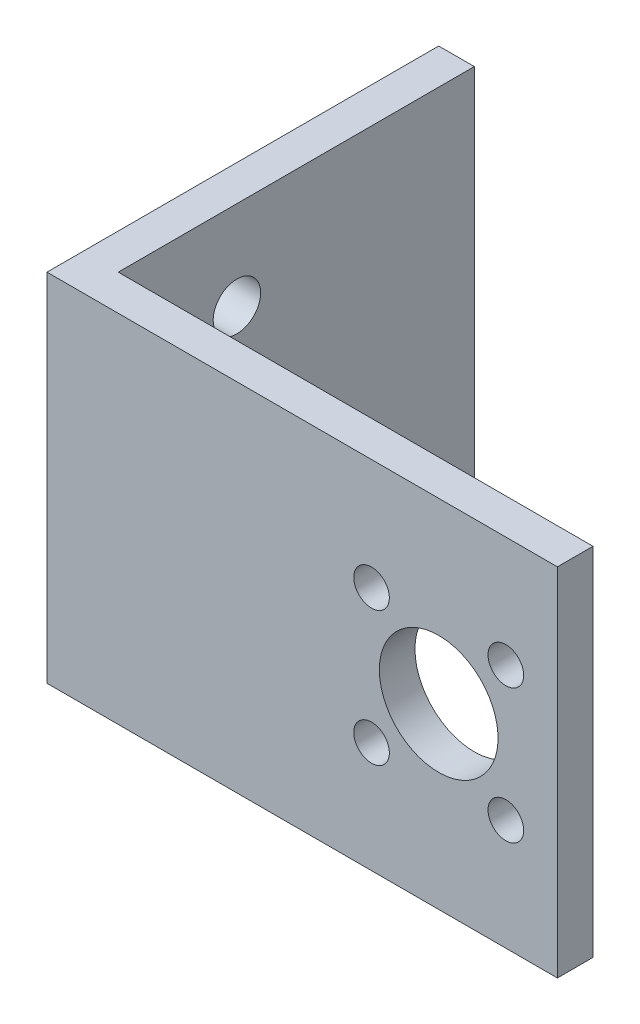
SolidWorks part; units mm, degrees
ref_plane "前视基准面" through (0, 0, 0) normal (0, 0, 1) x (1, 0, 0)
ref_plane "上视基准面" through (0, 0, 0) normal (0, 1, 0) x (1, 0, 0)
ref_plane "右视基准面" through (0, 0, 0) normal (1, 0, 0) x (0, 0, -1)
sketch "草图2" plane through (0, 0, 0) normal (0, 1, 0) x (1, 0, 0)
  line L0 (0, 0) -> (43, 0)
  line L1 (43, 0) -> (43, 3)
  line L2 (43, 3) -> (3, 3)
  line L3 (3, 3) -> (3, 33)
  line L4 (3, 33) -> (0, 33)
  line L5 (0, 33) -> (0, 0)
  dimension "D1" = 40
  dimension "D2" = 30
  dimension "D3" = 3
  dimension "D4" = 3
extrude "凸台-拉伸1" add sketch "草图2" along normal blind 30
sketch "草图4" plane through (0, 0, 0) normal (-1, 0, 0) x (0, 0, 1)
  line L0 (0, 30) -> (0, 0) construction
  line L1 (-33, 30) -> (0, 30) construction
  circle A0 centre (-13, 7.5) radius 2
  circle A1 centre (-13, 22.5) radius 2
  dimension "D2" = 7.5
  dimension "D3" = 4
  dimension "D1" = 13
  dimension "D4" = 15
extrude "切除-拉伸1" cut sketch "草图4" against normal up to next
sketch "草图5" plane through (0, 0, -3) normal (0, 0, -1) x (-1, 0, 0)
  line L0 (-43, 0) -> (-3, 0) construction
  line L1 (-3, 30) -> (-3, 0) construction
  line L2 (-43, 30) -> (-3, 30) construction
  circle A0 centre (-33, 15) radius 5
  circle A1 centre (-38.6569, 9.3431) radius 1.5
  circle A2 centre (-27.3431, 9.3431) radius 1.5
  circle A3 centre (-38.6569, 20.6569) radius 1.5
  circle A4 centre (-27.3431, 20.6569) radius 1.5
  dimension "D2" = 10
  dimension "D1" = 30
  dimension "D5" = 16
  dimension "D4" = 3
  dimension "D9" = 9.3431
  dimension "D10" = 3
  dimension "D11" = 3
  dimension "D12" = 3
  dimension "D3" = 15
  dimension "D6" = 8
  dimension "D7" = 16
  dimension "D8" = 8
  dimension "D13" = 9.3431
extrude "切除-拉伸2" cut sketch "草图5" against normal up to next
